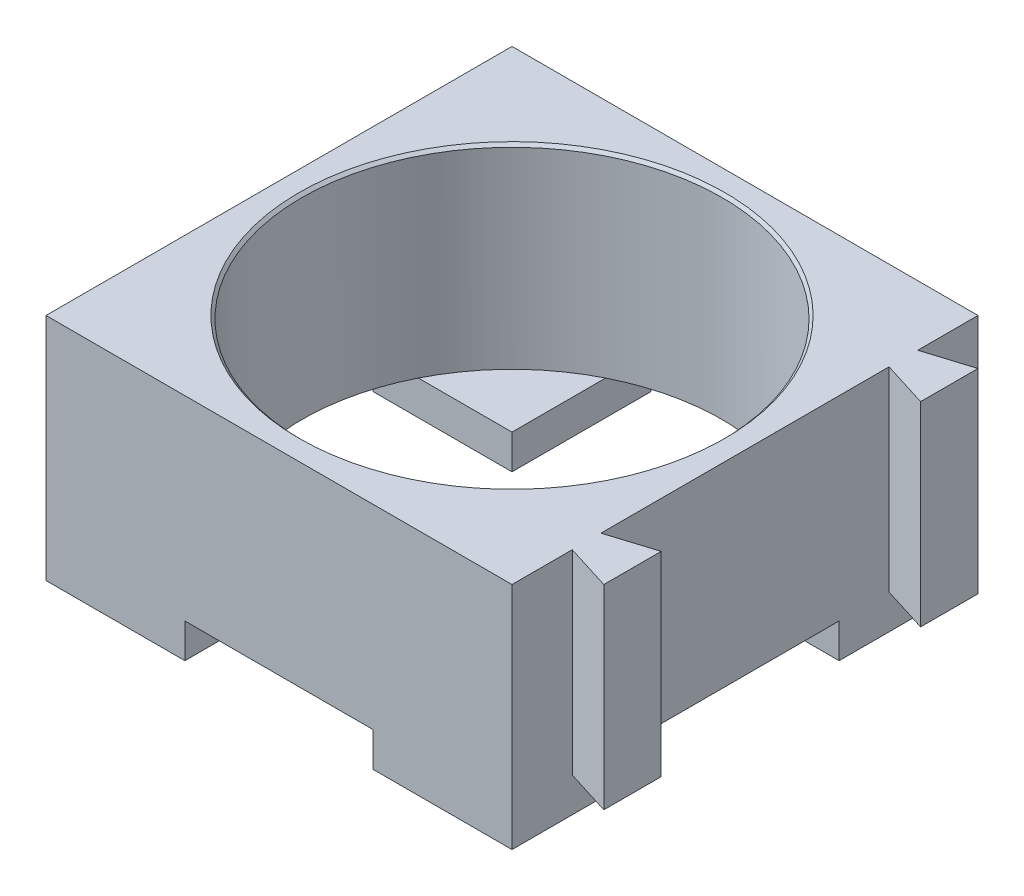
SolidWorks part; units mm, degrees
other "Referencias publicadas"
other "Conector1"
ref_plane "Front Plane" through (0, 0, 0) normal (0, 0, 1) x (1, 0, 0)
ref_plane "Top Plane" through (0, 0, 0) normal (0, 1, 0) x (1, 0, 0)
ref_plane "Right Plane" through (0, 0, 0) normal (1, 0, 0) x (0, 0, -1)
sketch "Sketch1" plane through (0, 0, 0) normal (0, 1, 0) x (1, 0, 0)
  line L0 (12.15, 8.15) -> (12.15, 5.65)
  line L1 (-10.15, 10.15) -> (10.15, 10.15)
  line L2 (-10.15, 10.15) -> (-10.15, -10.15)
  line L3 (-10.15, -10.15) -> (10.15, -10.15)
  line L4 (10.15, 10.15) -> (10.15, 7.525)
  line L5 (-10.15, 10.15) -> (10.15, -10.15) construction
  line L6 (-10.15, -10.15) -> (10.15, 10.15) construction
  line L7 (12.15, 5.65) -> (10.15, 6.275)
  line L8 (12.15, 8.15) -> (10.15, 7.525)
  line L9 (12.15, -5.65) -> (10.15, -6.275)
  line L10 (12.15, -5.65) -> (12.15, -8.15)
  line L11 (12.15, -8.15) -> (10.15, -7.525)
  line L12 (10.15, 6.275) -> (10.15, -6.275)
  line L13 (10.15, -7.525) -> (10.15, -10.15)
  circle A0 centre (0, 0) radius 9.15
  point P12 (12.15, 6.9)
  dimension "D1" = 18.3
  dimension "D2" = 20.3
  dimension "D3" = 20.3
  dimension "D4" = 2.5
  dimension "D5" = 1.25
  dimension "D6" = 0.625
  dimension "D7" = 2
  dimension "D8" = 2
  dimension "D10" = 2
  dimension "D9" = 2
extrude "Cell Holder " add sketch "Sketch1" along normal blind 8.5
sketch "Sketch2" plane through (0, 0, 0) normal (0, -1, 0) x (1, 0, 0)
  line L1 (-10.15, 10.15) -> (-4.1, 10.15)
  line L2 (-10.15, 10.15) -> (-10.15, 4.1)
  line L3 (-10.15, 4.1) -> (-4.1, 4.1)
  line L4 (-4.1, 10.15) -> (-4.1, 4.1)
  line L5 (-10.15, -10.15) -> (-4.1, -10.15)
  line L6 (-10.15, -10.15) -> (-10.15, -4.1)
  line L7 (-10.15, -4.1) -> (-4.1, -4.1)
  line L8 (-4.1, -10.15) -> (-4.1, -4.1)
  line L9 (10.15, 10.15) -> (4.1, 10.15)
  line L10 (10.15, 10.15) -> (10.15, 4.1)
  line L11 (10.15, 4.1) -> (4.1, 4.1)
  line L12 (4.1, 10.15) -> (4.1, 4.1)
  line L13 (10.15, -10.15) -> (4.1, -10.15)
  line L14 (10.15, -10.15) -> (10.15, -4.1)
  line L15 (10.15, -4.1) -> (4.1, -4.1)
  line L16 (4.1, -10.15) -> (4.1, -4.1)
  circle A0 centre (0, 0) radius 9.15 construction
  dimension "D1" = 8.2
  dimension "D2" = 4.1
  dimension "D3" = 8.2
  dimension "D4" = 4.1
extrude "Bottom Base Boss" add sketch "Sketch2" along normal blind 1.5
chamfer "Chamfer1" distance 0.125 angle 45 1 edges at (0, 8.5, 9.15)
